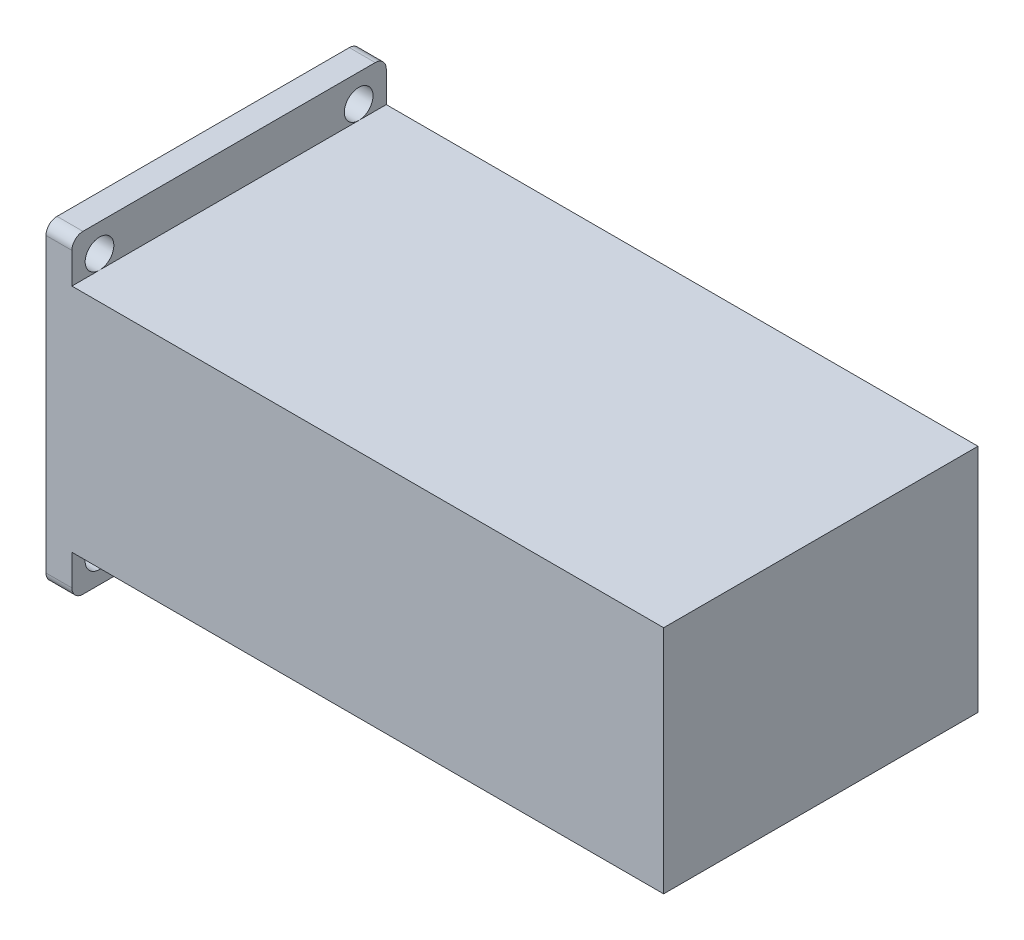
SolidWorks part; units mm, degrees
ref_plane "前视基准面" through (0, 0, 0) normal (0, 0, 1) x (1, 0, 0)
ref_plane "上视基准面" through (0, 0, 0) normal (0, 1, 0) x (1, 0, 0)
ref_plane "右视基准面" through (0, 0, 0) normal (1, 0, 0) x (0, 0, -1)
other "Configuration Table"
sketch "草图1" plane through (0, 0, 0) normal (1, 0, 0) x (0, 0, -1)
  line L1 (28.5, -28.5) -> (-28.5, -28.5)
  line L2 (28.5, -28.5) -> (28.5, 28.5)
  line L3 (28.5, 28.5) -> (-28.5, 28.5)
  line L4 (-28.5, -28.5) -> (-28.5, 28.5)
  line L5 (28.5, -28.5) -> (-28.5, 28.5) construction
  line L6 (28.5, 28.5) -> (-28.5, -28.5) construction
  point P0 (0, 0)
  dimension "D1" = 57
  dimension "D2" = 57
extrude "凸台-拉伸1" add sketch "草图1" along normal blind 112
fillet "圆角1" radius 2 4 edges at (56, -28.5, -28.5) (56, -28.5, 28.5) (56, 28.5, -28.5) (56, 28.5, 28.5)
sketch "草图5" plane through (112, 0, 0) normal (1, 0, 0) x (0, 0, -1)
  line L0 (-20.9, 20.9) -> (20.9, 20.9)
  line L1 (-28.5, 28.5) -> (28.5, 28.5)
  line L2 (-28.5, 28.5) -> (-28.5, 20.9)
  line L3 (-28.5, -28.5) -> (28.5, -28.5)
  line L4 (28.5, 28.5) -> (28.5, 20.9)
  line L6 (-20.9, -20.9) -> (20.9, -20.9)
  line L8 (-20.9, 20.9) -> (-28.5, 20.9)
  line L9 (-28.5, -20.9) -> (-20.9, -20.9)
  line L10 (20.9, 20.9) -> (28.5, 20.9)
  line L11 (20.9, -20.9) -> (28.5, -20.9)
  line L12 (-28.5, -20.9) -> (-28.5, -28.5)
  line L13 (20.9, 20.9) -> (20.9, -20.9) construction
  line L14 (-20.9, 20.9) -> (-20.9, -20.9) construction
  line L15 (-28.5, 28.5) -> (-28.5, -28.5) construction
  line L16 (28.5, -20.9) -> (28.5, -28.5)
  line L17 (28.5, 28.5) -> (28.5, -28.5) construction
  dimension "D1" = 7.6
extrude "切除-拉伸2" cut sketch "草图5" against normal blind 107.3
sketch "草图6" plane through (0, 0, 0) normal (-1, 0, 0) x (0, 0, 1)
  circle A0 centre (0, 0) radius 4
  dimension "D1" = 8
extrude "凸台-拉伸2" add sketch "草图6" along normal blind 20
sketch "草图7" plane through (-20, 0, 0) normal (-1, 0, 0) x (0, 0, 1)
  line L1 (-4.659, 4) -> (4.7837, 4)
  line L2 (-4.659, 4) -> (-4.659, 3.5)
  line L3 (-4.659, 3.5) -> (4.7837, 3.5)
  line L4 (4.7837, 4) -> (4.7837, 3.5)
  circle A0 centre (0, 0) radius 4 construction
  dimension "D1" = 0.5
  dimension "D2" = 4
extrude "切除-拉伸3" cut sketch "草图7" against normal blind 15
sketch "草图2" plane through (0, 0, 0) normal (-1, 0, 0) x (0, 0, 1)
  circle A0 centre (0, 0) radius 19.05
  dimension "D1" = 38.1
extrude "凸台-拉伸3" add sketch "草图2" along normal blind 1.5
sketch "草图8" plane through (0, 0, 0) normal (-1, 0, 0) x (0, 0, 1)
  line L0 (-28.5, -26.5) -> (-28.5, 26.5) construction
  line L1 (26.5, -28.5) -> (-26.5, -28.5) construction
  line L3 (-26.5, 28.5) -> (26.5, 28.5) construction
  circle A0 centre (-23.5, 23.5) radius 2.6
  circle A1 centre (23.5, 23.5) radius 2.6
  circle A2 centre (-23.5, -23.5) radius 2.6
  circle A3 centre (23.5, -23.5) radius 2.6
  dimension "D1" = 5.2
  dimension "D2" = 5.2
  dimension "D3" = 47
  dimension "D4" = 5
  dimension "D5" = 5
  dimension "D6" = 5
  dimension "D7" = 47
  dimension "D8" = 5.2
  dimension "D9" = 5
extrude "切除-拉伸4" cut sketch "草图8" against normal up to surface (4.7 mm away) up to face at (4.7, 25.4381, 0)
